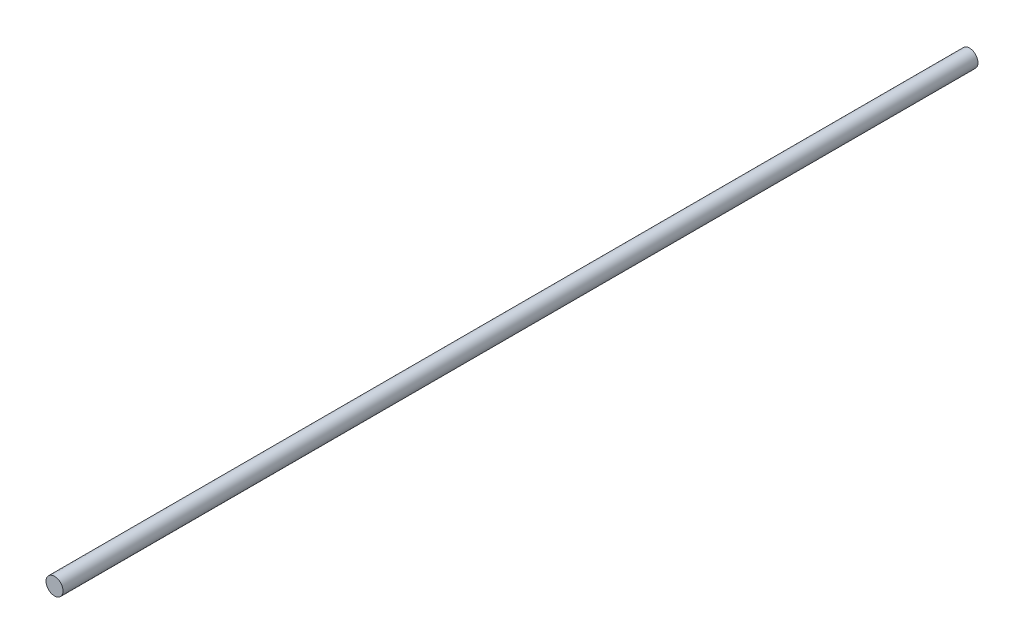
SolidWorks part; units mm, degrees
material "Alliage 1060"
ref_plane "Front Plane" through (0, 0, 0) normal (0, 0, 1) x (1, 0, 0)
ref_plane "Top Plane" through (0, 0, 0) normal (0, 1, 0) x (1, 0, 0)
ref_plane "Right Plane" through (0, 0, 0) normal (1, 0, 0) x (0, 0, -1)
sketch "Sketch1" plane through (0, 0, 0) normal (0, 0, 1) x (1, 0, 0)
  circle A0 centre (0, 0) radius 4
  dimension "D1" = 8
extrude "Boss-Extrude1" add sketch "Sketch1" along normal blind 430
